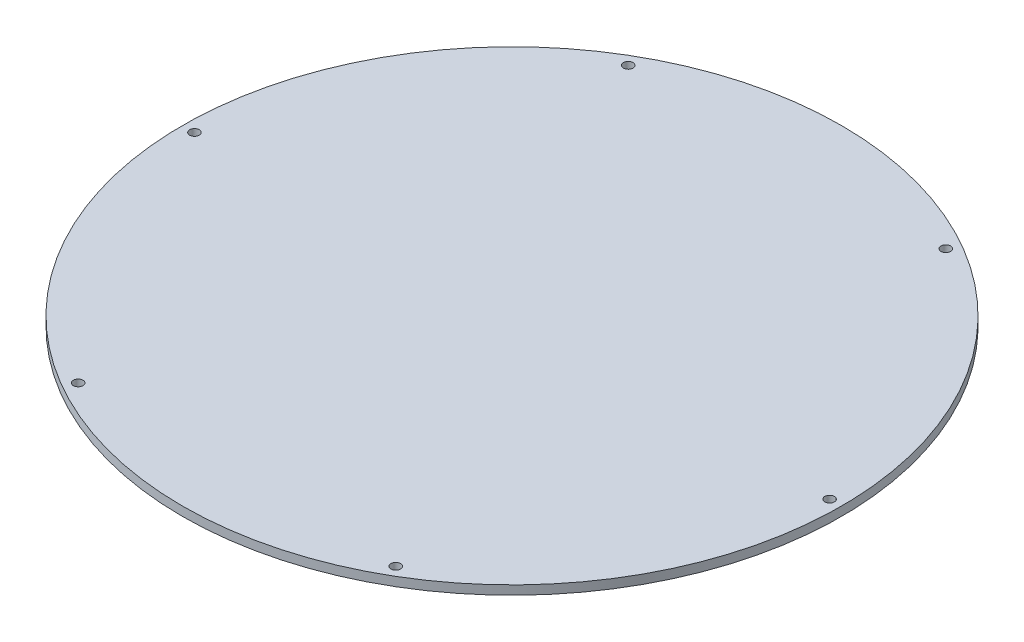
SolidWorks part; units mm, degrees
ref_plane "Front Plane" through (0, 0, 0) normal (0, 0, 1) x (1, 0, 0)
ref_plane "Top Plane" through (0, 0, 0) normal (0, 1, 0) x (1, 0, 0)
ref_plane "Right Plane" through (0, 0, 0) normal (1, 0, 0) x (0, 0, -1)
sketch "Sketch1" plane through (0, 0, 0) normal (0, 1, 0) x (1, 0, 0)
  circle A0 centre (0, 0) radius 110
  dimension "D1" = 220
extrude "Boss-Extrude1" add sketch "Sketch1" along normal blind 3
sketch "Sketch2" plane through (0, 3, 0) normal (0, 1, 0) x (1, 0, 0)
  line L0 (0, 0) -> (0, 106) construction
  line L1 (0, 0) -> (53, 91.7987) construction
  circle A0 centre (0, 0) radius 106
  circle A1 centre (53, 91.7987) radius 1.6
  circle A2 centre (106, 0) radius 1.6
  circle A3 centre (53, -91.7987) radius 1.6
  circle A4 centre (-53, -91.7987) radius 1.6
  circle A5 centre (-106, 0) radius 1.6
  circle A6 centre (-53, 91.7987) radius 1.6
  dimension "D1" = 212
  dimension "D2" = 3.2
  dimension "D4" = 30
  dimension "D3" = 6
extrude "Cut-Extrude1" cut sketch "Sketch2" against normal blind 3 contours A0 A1 | A0 A1 | A0 A2 | A0 A2 | A0 A3 | A0 A3 | A0 A4 | A0 A4 | A0 A5 | A0 A5 | A0 A6 | A0 A6
